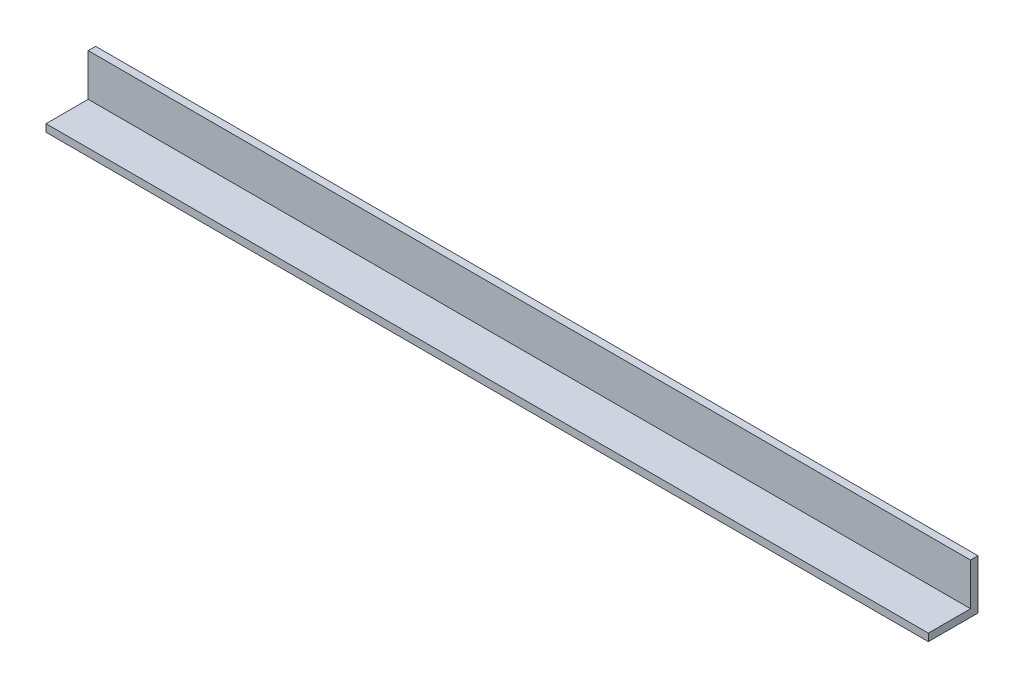
SolidWorks part; units mm, degrees
ref_plane "前视基准面" through (0, 0, 0) normal (0, 0, 1) x (1, 0, 0)
ref_plane "上视基准面" through (0, 0, 0) normal (0, 1, 0) x (1, 0, 0)
ref_plane "右视基准面" through (0, 0, 0) normal (1, 0, 0) x (0, 0, -1)
sketch "草图1" plane through (0, 0, 0) normal (0, 0, 1) x (1, 0, 0)
  line L1 (0, 0) -> (1422, 0)
  line L2 (0, 0) -> (0, 80)
  line L3 (0, 80) -> (1422, 80)
  line L4 (1422, 0) -> (1422, 80)
  dimension "D1" = 1422
  dimension "D2" = 80
extrude "拉伸1" add sketch "草图1" along normal blind 80
sketch "草图3" plane through (0, 0, 0) normal (-1, 0, 0) x (0, 0, 1)
  line L0 (80, 80) -> (80, 0) construction
  line L1 (12, 80) -> (80, 80)
  line L2 (12, 80) -> (12, 12)
  line L3 (12, 12) -> (80, 12)
  line L4 (80, 80) -> (80, 12)
  line L5 (80, 80) -> (0, 80) construction
  line L6 (80, 0) -> (0, 0) construction
  line L7 (0, 80) -> (0, 0) construction
  dimension "D1" = 12
  dimension "D2" = 12
extrude "拉伸2" cut sketch "草图3" against normal through all
